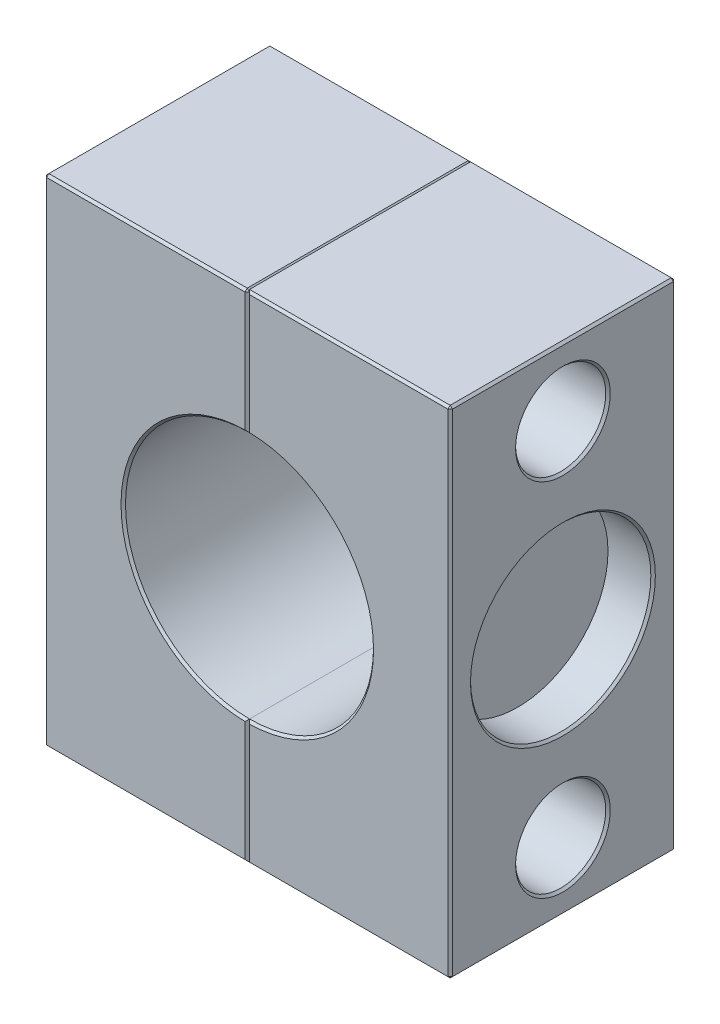
SolidWorks part; units mm, degrees
ref_plane "Front Plane" through (0, 0, 0) normal (0, 0, 1) x (1, 0, 0)
ref_plane "Top Plane" through (0, 0, 0) normal (0, 1, 0) x (1, 0, 0)
ref_plane "Right Plane" through (0, 0, 0) normal (1, 0, 0) x (0, 0, -1)
sketch "Sketch1" plane through (0, 0, 0) normal (0, 0, 1) x (1, 0, 0)
  line L0 (0, 11) -> (0, 0)
  line L1 (9, -11) -> (-9, -11)
  line L2 (9, -11) -> (9, 11)
  line L3 (9, 11) -> (-9, 11)
  line L4 (-9, -11) -> (-9, 11)
  line L5 (9, -11) -> (-9, 11) construction
  line L6 (9, 11) -> (-9, -11) construction
  line L7 (0, 0) -> (0, -11)
  circle A0 centre (0, 0) radius 5.5
  point P0 (0, 0)
  dimension "D1" = 11
  dimension "D2" = 18
  dimension "D3" = 22
extrude "Boss-Extrude1" add sketch "Sketch1" along normal mid plane 10 contours A0 L0 L3 L4 L1 L7
sketch "Sketch3" plane through (0, 0, 0) normal (0, 0, 1) x (1, 0, 0)
  line L0 (0, 11) -> (0, 0) construction
  line L1 (0, 0) -> (0, -11) construction
  line L2 (0, 11) -> (0, 0)
  line L3 (0, 0) -> (0, -11)
  line L4 (-9, -11) -> (9, -11)
  line L5 (-9, 11) -> (-9, -11)
  line L6 (9, 11) -> (-9, 11)
  line L7 (9, -11) -> (9, 11)
  line L8 (-9, -11) -> (9, -11)
  line L9 (-9, 11) -> (-9, -11)
  line L10 (9, 11) -> (-9, 11)
  line L11 (9, -11) -> (9, 11)
  circle A1 centre (0, 0) radius 5.5
  circle A2 centre (0, 0) radius 5.5
  dimension "D1" = 0
  dimension "D2" = 0
extrude "Boss-Extrude2" add sketch "Sketch3" along normal mid plane 10 separate body contours A2 L3 L8 L11 L10 L2
sketch "Sketch4" plane through (9, 0, 0) normal (1, 0, 0) x (0, 0, -1)
  line L0 (-5, -11) -> (5, -11) construction
  line L2 (-5, 11) -> (5, 11) construction
  circle A0 centre (0, 8) radius 2
  circle A1 centre (0, -8) radius 2
  dimension "D1" = 4
  dimension "D2" = 4
  dimension "D3" = 3
  dimension "D4" = 8
  dimension "D5" = 8
  dimension "D6" = 3
extrude "Cut-Extrude3" cut sketch "Sketch4" against normal through all
sketch "Sketch5" plane through (9, 0, 0) normal (1, 0, 0) x (0, 0, -1)
  circle A0 centre (0, 0) radius 4
  dimension "D1" = 8
extrude "Cut-Extrude4" cut sketch "Sketch5" against normal blind 2
chamfer "Chamfer1" distance 0.1 angle 45 14 edges at (9, -11, 0) (0, 8.25, 5) (4.5, 11, 5) (5.5, 0, 5) (0, -8.25, 5) (4.5, -11, 5) (9, 0, 5) (9, 11, 0) (0, -8.25, -5) (4.5, -11, -5) (9, 0, -5) (4.5, 11, -5) (0, 8.25, -5) (5.5, 0, -5)
chamfer "Chamfer2" distance 0.1 angle 45 17 edges at (-9, -8, -2) (-9, 8, -2) (-9, -11, 0) (0, 8.25, -5) (-5.5, 0, -5) (0, -8.25, -5) (-4.5, -11, -5) (-9, 0, -5) (0, 11, 0) (-4.5, 11, -5) (-9, 11, 0) (0, -8.25, 5) (-4.5, -11, 5) (-9, 0, 5) (-4.5, 11, 5) (0, 8.25, 5) (-5.5, 0, 5)
chamfer "Chamfer3" distance 0.1 angle 45 3 edges at (9, -8, -2) (9, 8, -2) (9, 0, -4)
